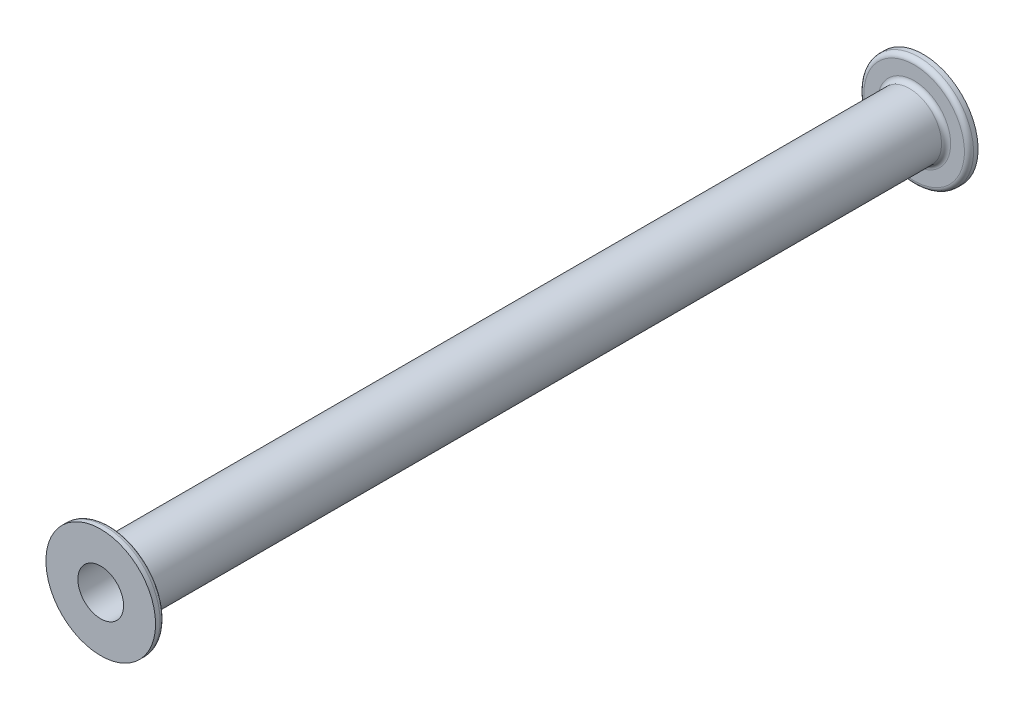
SolidWorks part; units mm, degrees
material "6061 合金"
ref_plane "前视基准面" through (0, 0, 0) normal (0, 0, 1) x (1, 0, 0)
ref_plane "上视基准面" through (0, 0, 0) normal (0, 1, 0) x (1, 0, 0)
ref_plane "右视基准面" through (0, 0, 0) normal (1, 0, 0) x (0, 0, -1)
other "Configuration Table"
sketch "草图1" plane through (0, 0, 0) normal (0, 0, 1) x (1, 0, 0)
  circle A0 centre (0, 0) radius 2.5
  circle A1 centre (0, 0) radius 3.5
  dimension "D1" = 5
  dimension "D2" = 7
extrude "凸台-拉伸1" add sketch "草图1" along normal blind 90 contours A0 | A1
sketch "草图2" plane through (0, 0, 0) normal (0, 0, -1) x (-1, 0, 0)
  circle A0 centre (0, 0) radius 6
  circle A1 centre (0, 0) radius 2.5 construction
  circle A2 centre (0, 0) radius 2.5
  dimension "D1" = 12
extrude "凸台-拉伸2" add sketch "草图2" against normal blind 1
sketch "草图3" plane through (0, 0, 90) normal (0, 0, 1) x (1, 0, 0)
  circle A1 centre (0, 0) radius 2.5 construction
  circle A2 centre (0, 0) radius 2.5
  circle A3 centre (0, 0) radius 6 construction
  circle A4 centre (0, 0) radius 6
extrude "凸台-拉伸3" add sketch "草图3" against normal blind 1
fillet "圆角1" radius 0.5 4 edges at (6, 0, 89) (3.5, 0, 89) (-3.5, 0, 1) (-6, 0, 1)
